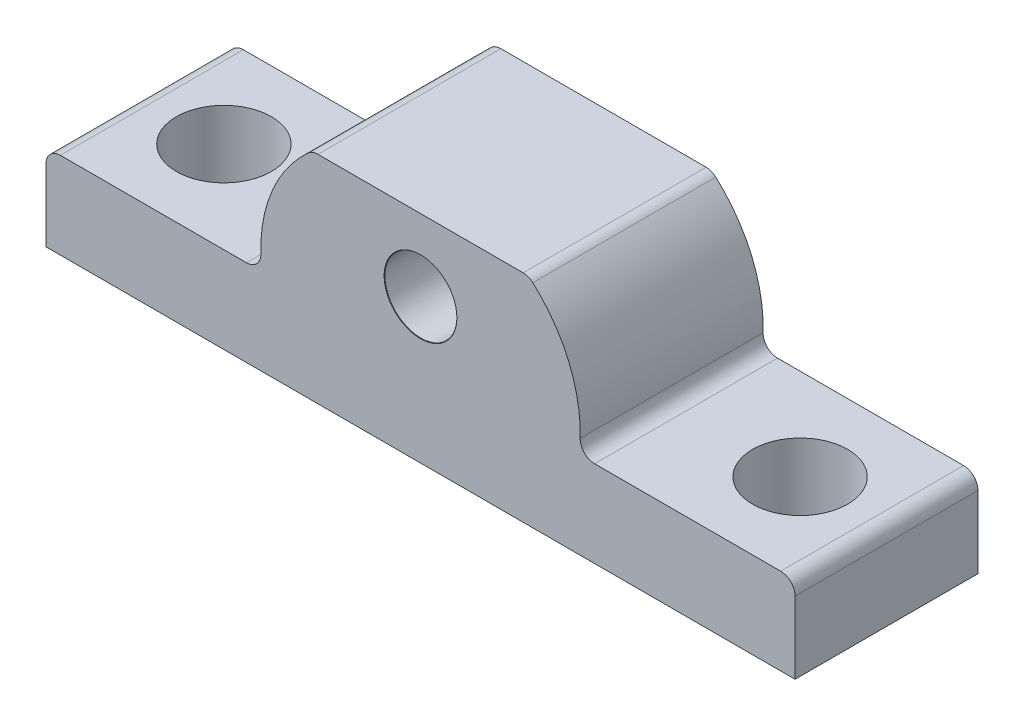
SolidWorks part; units mm, degrees
material "6061 Alloy"
ref_plane "Front Plane" through (0, 0, 0) normal (0, 0, 1) x (1, 0, 0)
ref_plane "Top Plane" through (0, 0, 0) normal (0, 1, 0) x (1, 0, 0)
ref_plane "Right Plane" through (0, 0, 0) normal (1, 0, 0) x (0, 0, -1)
sketch "Sketch1" plane through (0, 0, 0) normal (0, 0, 1) x (1, 0, 0)
  line L0 (-26, 0) -> (26, 0)
  line L1 (26, 0) -> (26, 6)
  line L2 (26, 6) -> (11, 6)
  line L3 (-26, 0) -> (-26, 6)
  line L4 (-26, 6) -> (-11, 6)
  line L5 (7.5, 15) -> (-7.5, 15)
  arc A0 (-11, 6) -> (-7.5, 15) centre (-1.0883, 7.326) cw
  arc A1 (11, 6) -> (7.5, 15) centre (1.0883, 7.326) ccw
  circle A2 centre (0, 10) radius 3 construction
  point P12 (0, 0)
  point P13 (0, 15)
  dimension "D6" = 10
  dimension "D8" = 6
  dimension "D1" = 6
  dimension "D2" = 52
  dimension "D3" = 15
  dimension "D4" = 15
  dimension "D5" = 15
  dimension "D7" = 10
extrude "Boss-Extrude1" add sketch "Sketch1" against normal blind 12.7 contours A0 L5 A1 L2 L1 L0 L3 L4
hole_wizard "Tap Drill for M6x1.0 Tap1" positions "3DSketch1" profile "Sketch2" hole size "M6x1.0" standard "ANSI Metric" end condition through all
sketch3d "3DSketch1"
  point P0 (0, 10, 0)
sketch "Sketch2" plane through (0, 10, 0) normal (1, 0, 0) x (0, -1, 0)
  line L0 (0, 0) -> (0, 12.7)
  line L1 (0, 12.7) -> (2.5, 12.7)
  line L2 (2.5, 12.7) -> (2.5, 0.025)
  line L3 (2.5, 0.025) -> (2.525, 0)
  line L5 (2.525, 0) -> (0, 0)
  line L6 (-2.5, 0.025) -> (-2.525, 0) construction
  line L11 (0, -6.35) -> (0, 107.95) construction
  dimension "Thru Hole Dia." = 5
  dimension "Thru Hole Depth" = 12.7
  dimension "Near C'Sink Dia." = 5.05
  dimension "Near C'Sink Angle" = 90
sketch "Sketch3" plane through (0, 0, 0) normal (0, -1, 0) x (1, 0, 0)
  line L0 (0, 0) -> (0, -12.7) construction
  line L1 (-26, -12.7) -> (26, -12.7) construction
  circle A0 centre (-20, -6.35) radius 3 construction
  circle A1 centre (20, -6.35) radius 3 construction
  point P8 (0, -6.35)
  dimension "D1" = 6
  dimension "D2" = 40
hole_wizard "M6 Clearance Hole1" positions "3DSketch2" profile "Sketch4" hole size "M6" standard "ANSI Metric" end condition through all
sketch3d "3DSketch2"
  point P0 (-20, 0, -6.35)
  point P2 (20, 0, -6.35)
sketch "Sketch4" plane through (-20, 0, -6.35) normal (1, 0, 0) x (0, 0, -1)
  line L0 (0, 0) -> (0, 15)
  line L1 (0, 15) -> (3.3, 15)
  line L2 (3.3, 15) -> (3.3, 0.025)
  line L3 (3.3, 0.025) -> (3.325, 0)
  line L5 (3.325, 0) -> (0, 0)
  line L6 (-3.3, 0.025) -> (-3.325, 0) construction
  line L11 (0, -6.35) -> (0, 107.95) construction
  dimension "Thru Hole Dia." = 6.6
  dimension "Thru Hole Depth" = 15
  dimension "Near C'Sink Dia." = 6.65
  dimension "Near C'Sink Angle" = 90
fillet "Fillet1" radius 1 6 edges at (-7.5, 15, -6.35) (7.5, 15, -6.35) (11, 6, -6.35) (-11, 6, -6.35) (26, 6, -6.35) (-26, 6, -6.35)
